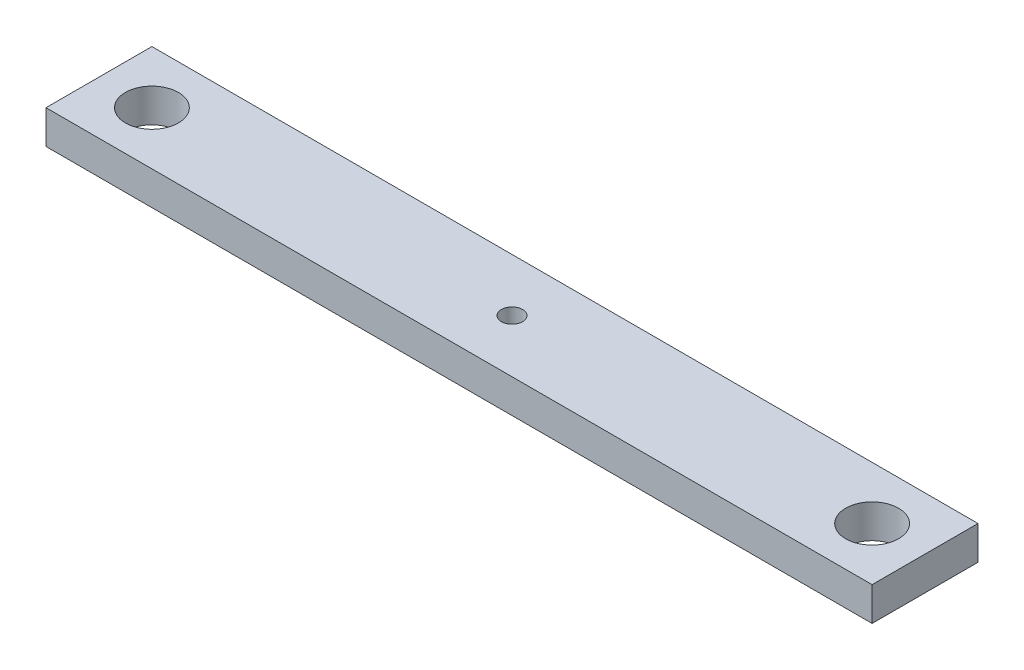
SolidWorks part; units mm, degrees
ref_plane "Front Plane" through (0, 0, 0) normal (0, 0, 1) x (1, 0, 0)
ref_plane "Top Plane" through (0, 0, 0) normal (0, 1, 0) x (1, 0, 0)
ref_plane "Right Plane" through (0, 0, 0) normal (1, 0, 0) x (0, 0, -1)
sketch "Sketch2" plane through (0, 0, 0) normal (0, 1, 0) x (1, 0, 0)
  line L1 (-39, -5) -> (39, -5)
  line L2 (-39, -5) -> (-39, 5)
  line L3 (-39, 5) -> (39, 5)
  line L4 (39, -5) -> (39, 5)
  line L5 (-39, -5) -> (39, 5) construction
  line L6 (-39, 5) -> (39, -5) construction
  point P0 (0, 0)
  dimension "D1" = 78
  dimension "D2" = 10
extrude "Boss-Extrude1" add sketch "Sketch2" along normal blind 3.175
sketch "Sketch3" plane through (0, 3.175, 0) normal (0, 1, 0) x (1, 0, 0)
  line L0 (-64.0944, 0) -> (61.2196, 0) construction
  line L1 (0, 21.5935) -> (0, -26.8203) construction
  circle A0 centre (-34, 0) radius 2.5
  circle A1 centre (34, 0) radius 2.5
  dimension "D1" = 5
  dimension "D2" = 34
extrude "Cut-Extrude1" cut sketch "Sketch3" against normal up to surface (3.175 mm away) up to face at (0, 0, 0)
sketch "Sketch4" plane through (0, 3.175, 0) normal (0, 1, 0) x (1, 0, 0)
  line L0 (0, -5) -> (0, 5) construction
  line L1 (-39, -5) -> (39, -5) construction
  line L2 (39, 5) -> (-39, 5) construction
  circle A0 centre (0, 0) radius 1
  dimension "D1" = 2
extrude "Cut-Extrude2" cut sketch "Sketch4" against normal up to next
